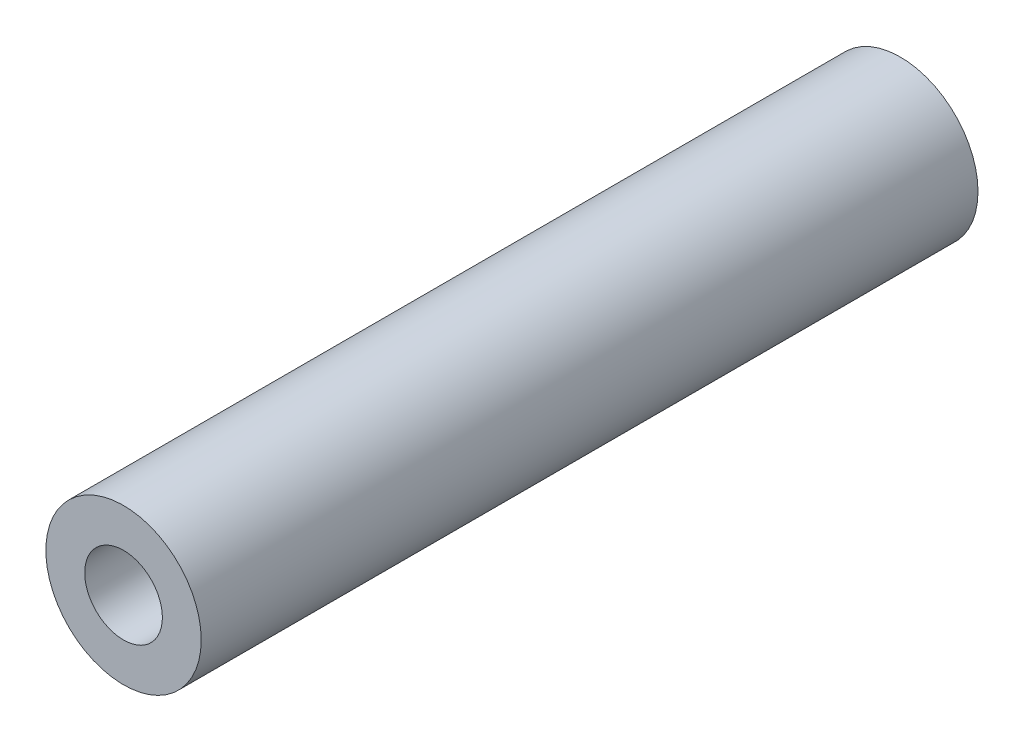
SolidWorks part; units mm, degrees
ref_plane "Front Plane" through (0, 0, 0) normal (0, 0, 1) x (1, 0, 0)
ref_plane "Top Plane" through (0, 0, 0) normal (0, 1, 0) x (1, 0, 0)
ref_plane "Right Plane" through (0, 0, 0) normal (1, 0, 0) x (0, 0, -1)
sketch "Sketch1" plane through (0, 0, 0) normal (0, 0, 1) x (1, 0, 0)
  circle A0 centre (0, 0) radius 5
  dimension "D1" = 10
extrude "Boss-Extrude1" add sketch "Sketch1" along normal blind 50
sketch "Sketch2" plane through (0, 0, 0) normal (0, 0, -1) x (-1, 0, 0)
  circle A0 centre (0, 0) radius 2.5
  dimension "D1" = 5
extrude "Cut-Extrude1" cut sketch "Sketch2" against normal blind 8
sketch "Sketch3" plane through (0, 0, 50) normal (0, 0, 1) x (1, 0, 0)
  circle A0 centre (0, 0) radius 2.5
  dimension "D1" = 5
extrude "Cut-Extrude2" cut sketch "Sketch3" against normal blind 8
